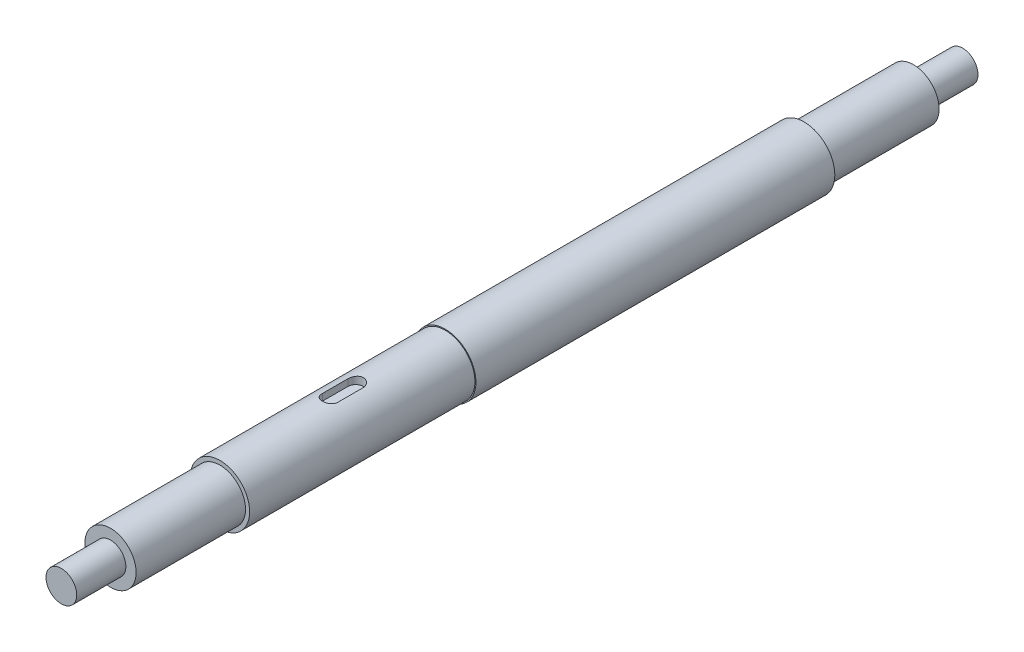
SolidWorks part; units mm, degrees
material "Alloy Steel"
ref_plane "Front Plane" through (0, 0, 0) normal (0, 0, 1) x (1, 0, 0)
ref_plane "Top Plane" through (0, 0, 0) normal (0, 1, 0) x (1, 0, 0)
ref_plane "Right Plane" through (0, 0, 0) normal (1, 0, 0) x (0, 0, -1)
sketch "Sketch1" plane through (0, 0, 0) normal (0, 0, 1) x (1, 0, 0)
  circle A0 centre (0, 0) radius 9.525
  dimension "D1" = 19.05
extrude "Boss-Extrude1" add sketch "Sketch1" along normal mid plane 279.4
ref_plane "Plane1" through (0, 0, 90.551) normal (0, 0, 1) x (1, 0, 0)
sketch "Sketch3" plane through (0, 0, 90.551) normal (0, 0, 1) x (1, 0, 0)
  circle A0 centre (0, 0) radius 7.9375
  circle A1 centre (0, 0) radius 9.525
  circle A2 centre (0, 0) radius 9.525
  dimension "D2" = 15.875
  dimension "D1" = 0
extrude "Cut-Extrude1" cut sketch "Sketch3" along normal up to next
mirror "Mirror1" about plane through (0, 0, 0) normal (0, 0, 1) of "Cut-Extrude1"
ref_plane "Plane2" through (0, 0, 124.46) normal (0, 0, 1) x (1, 0, 0)
sketch "Sketch4" plane through (0, 0, 124.46) normal (0, 0, 1) x (1, 0, 0)
  circle A0 centre (0, 0) radius 4.7625
  circle A1 centre (0, 0) radius 7.9375
  circle A2 centre (0, 0) radius 7.9375
  dimension "D2" = 9.525
  dimension "D1" = 0
extrude "Cut-Extrude2" cut sketch "Sketch4" along normal up to next
mirror "Mirror2" about plane through (0, 0, 0) normal (0, 0, 1) of "Cut-Extrude2"
sketch "Sketch5" plane through (0, 0, 90.551) normal (0, 0, 1) x (1, 0, 0)
  circle A0 centre (0, 0) radius 9.525 construction
  circle A1 centre (0, 0) radius 9.525
  circle A2 centre (0, 0) radius 9.2075
  dimension "D1" = 18.415
extrude "Cut-Extrude3" cut sketch "Sketch5" against normal blind 69.85
ref_plane "Plane3" through (0, 9.2075, 0) normal (0, 1, 0) x (1, 0, 0)
sketch "Sketch6" plane through (0, 9.2075, 0) normal (0, 1, 0) x (1, 0, 0)
  line L0 (-9.525, -20.701) -> (9.525, -20.701) construction
  line L1 (-9.2075, -90.551) -> (9.2075, -90.551) construction
  line L2 (-9.525, -20.701) -> (9.525, -20.701)
  line L3 (-9.2075, -90.551) -> (9.2075, -90.551)
  line L4 (0, -90.551) -> (0, -20.701) construction
  line L5 (-9.2075, -55.626) -> (9.2075, -55.626) construction
  line L6 (-9.2075, -20.701) -> (-9.2075, -90.551) construction
  line L7 (9.2075, -90.551) -> (9.2075, -20.701) construction
  line L8 (0, -56.4197) -> (0, -48.4822) construction
  line L9 (-2.3812, -56.4197) -> (-2.3813, -48.4822)
  line L10 (2.3813, -56.4197) -> (2.3812, -48.4822)
  line L11 (0, -46.101) -> (-5.2744, -46.101) construction
  line L12 (0, -58.801) -> (-5.6689, -58.801) construction
  arc A0 (-2.3812, -56.4197) -> (2.3813, -56.4197) centre (0, -56.4197) ccw
  arc A1 (2.3812, -48.4822) -> (-2.3813, -48.4822) centre (0, -48.4822) ccw
  point P14 (0, -52.451)
  dimension "D1" = 4.7625
  dimension "D2" = 12.7
  dimension "D3" = 38.1
extrude "Cut-Extrude4" cut sketch "Sketch6" against normal blind 2.3812 contours L10 A1 L9 A0
